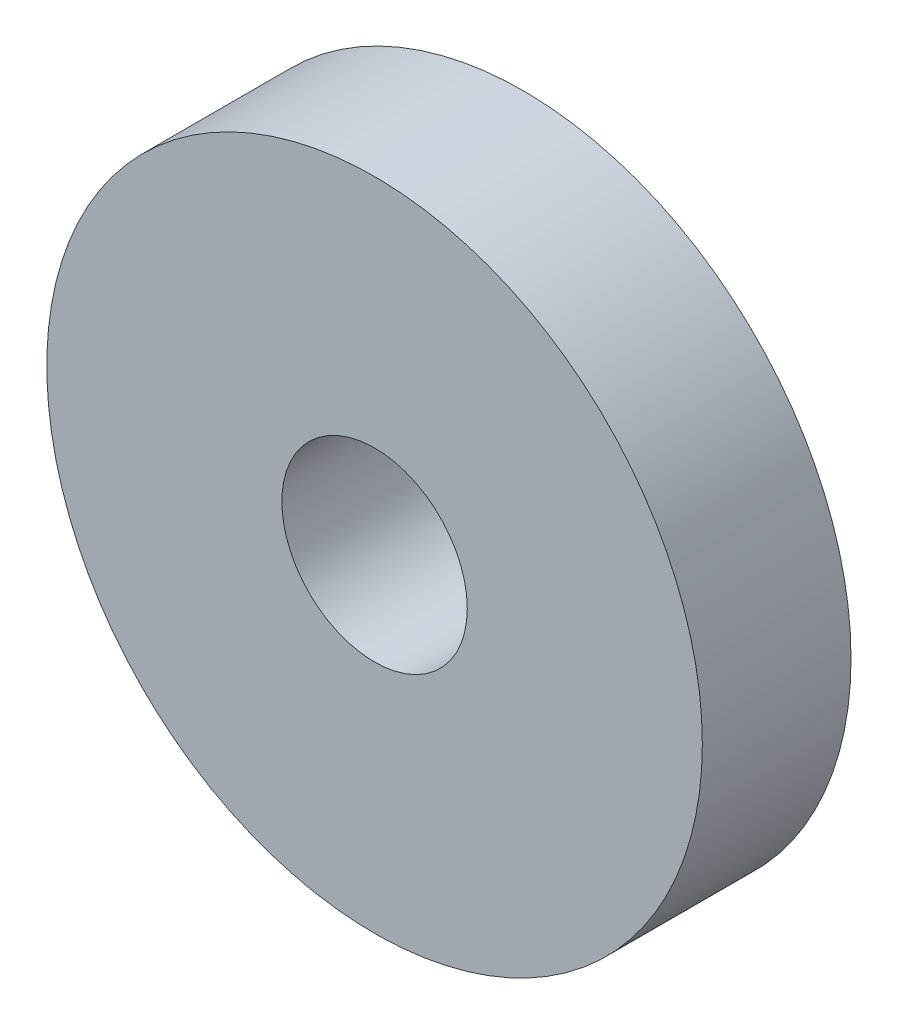
SolidWorks part; units mm, degrees
ref_plane "Plan de face" through (0, 0, 0) normal (0, 0, 1) x (1, 0, 0)
ref_plane "Plan de dessus" through (0, 0, 0) normal (0, 1, 0) x (1, 0, 0)
ref_plane "Plan de droite" through (0, 0, 0) normal (1, 0, 0) x (0, 0, -1)
sketch "Esquisse1" plane through (0, 0, 0) normal (0, 0, 1) x (1, 0, 0)
  circle A0 centre (0, 0) radius 14
  circle A1 centre (0, 0) radius 3.96
  dimension "D1" = 28
  dimension "D2" = 7.92
extrude "Boss.-Extru.1" add sketch "Esquisse1" along normal blind 6.35
